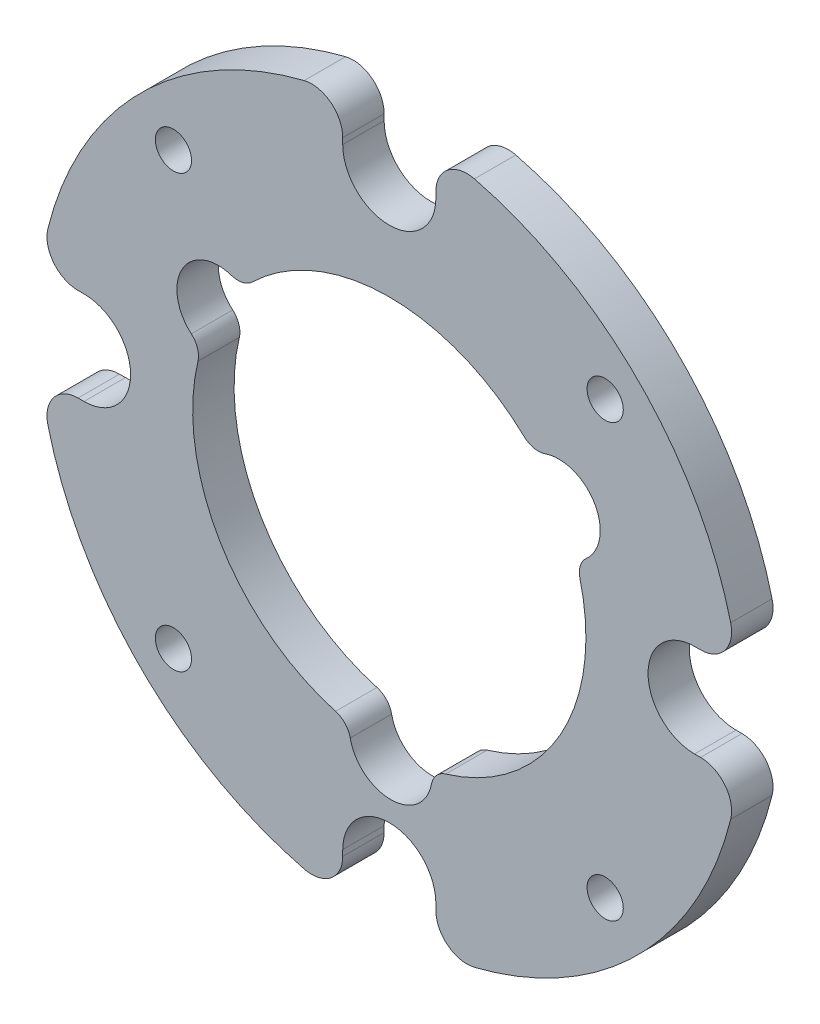
SolidWorks part; units mm, degrees
ref_plane "Спереди" through (0, 0, 0) normal (0, 0, 1) x (1, 0, 0)
ref_plane "Сверху" through (0, 0, 0) normal (0, 1, 0) x (1, 0, 0)
ref_plane "Справа" through (0, 0, 0) normal (1, 0, 0) x (0, 0, -1)
sketch "Sketch1" plane through (0, 0, 0) normal (0, 0, 1) x (1, 0, 0)
  line L0 (3.9, 6.755) -> (7.8, 0) construction
  line L2 (5.85, 10.1325) -> (11.7, 0) construction
  line L4 (7.8, 13.51) -> (15.6, 0) construction
  circle A61 centre (0, 0) radius 20
  circle A131 centre (0, 0) radius 1.25
  circle A484 centre (3.9, 0) radius 1.25
  circle A485 centre (7.8, 0) radius 1.25
  circle A486 centre (11.7, 0) radius 1.25
  circle A487 centre (15.6, 0) radius 1.25
  circle A488 centre (1.95, -3.3775) radius 1.25
  circle A489 centre (3.9, -6.755) radius 1.25
  circle A490 centre (5.85, -10.1325) radius 1.25
  circle A491 centre (7.8, -13.51) radius 1.25
  circle A492 centre (-1.95, -3.3775) radius 1.25
  circle A493 centre (-3.9, -6.755) radius 1.25
  circle A494 centre (-5.85, -10.1325) radius 1.25
  circle A495 centre (-7.8, -13.51) radius 1.25
  circle A496 centre (-3.9, 0) radius 1.25
  circle A497 centre (-7.8, 0) radius 1.25
  circle A498 centre (-11.7, 0) radius 1.25
  circle A499 centre (-15.6, 0) radius 1.25
  circle A500 centre (-1.95, 3.3775) radius 1.25
  circle A501 centre (-3.9, 6.755) radius 1.25
  circle A502 centre (-5.85, 10.1325) radius 1.25
  circle A503 centre (-7.8, 13.51) radius 1.25
  circle A504 centre (1.95, 3.3775) radius 1.25
  circle A505 centre (3.9, 6.755) radius 1.25
  circle A506 centre (5.85, 10.1325) radius 1.25
  circle A507 centre (7.8, 13.51) radius 1.25
  circle A508 centre (5.85, 3.3775) radius 1.25
  circle A509 centre (7.8, 6.755) radius 1.25
  circle A510 centre (9.75, 3.3775) radius 1.25
  circle A511 centre (11.7, 6.755) radius 1.25
  circle A512 centre (9.7491, 10.1341) radius 1.25
  circle A513 centre (13.6509, 3.3759) radius 1.25
  circle A514 centre (5.85, -3.3791) radius 1.25
  circle A515 centre (9.75, -3.3791) radius 1.25
  circle A516 centre (7.8, -6.7566) radius 1.25
  circle A517 centre (11.7, -6.7566) radius 1.25
  circle A518 centre (9.7491, -10.1356) radius 1.25
  circle A519 centre (13.6509, -3.3775) radius 1.25
  circle A520 centre (-0.0013, -6.7573) radius 1.25
  circle A521 centre (1.9487, -10.1348) radius 1.25
  circle A522 centre (-1.9513, -10.1348) radius 1.25
  circle A523 centre (-0.0013, -13.5123) radius 1.25
  circle A524 centre (-3.9032, -13.5123) radius 1.25
  circle A525 centre (3.9005, -13.5123) radius 1.25
  circle A526 centre (-5.8527, -3.3791) radius 1.25
  circle A527 centre (-7.8027, -6.7566) radius 1.25
  circle A528 centre (-9.7527, -3.3791) radius 1.25
  circle A529 centre (-11.7027, -6.7566) radius 1.25
  circle A530 centre (-13.6536, -3.3775) radius 1.25
  circle A531 centre (-9.7518, -10.1356) radius 1.25
  circle A532 centre (-5.8527, 3.3775) radius 1.25
  circle A533 centre (-9.7527, 3.3775) radius 1.25
  circle A534 centre (-7.8027, 6.755) radius 1.25
  circle A535 centre (-11.7027, 6.755) radius 1.25
  circle A536 centre (-9.7518, 10.1341) radius 1.25
  circle A537 centre (-13.6536, 3.3759) radius 1.25
  circle A538 centre (-0.0014, 6.7558) radius 1.25
  circle A539 centre (-1.9514, 10.1333) radius 1.25
  circle A540 centre (1.9486, 10.1333) radius 1.25
  circle A541 centre (-0.0014, 13.5108) radius 1.25
  circle A542 centre (3.9005, 13.5108) radius 1.25
  circle A543 centre (-3.9032, 13.5108) radius 1.25
  circle A544 centre (13.65, -1.1258) radius 2.2517 construction
  circle A545 centre (11.7009, -4.5044) radius 2.2522 construction
  circle A546 centre (9.75, -7.8834) radius 2.2522 construction
  circle A547 centre (7.7987, -11.2591) radius 2.2509 construction
  circle A548 centre (13.65, -1.1258) radius 0.65
  circle A549 centre (11.7009, -4.5044) radius 0.65
  circle A550 centre (9.75, -7.8834) radius 0.65
  circle A551 centre (7.7987, -11.2591) radius 0.65
  circle A552 centre (9.75, -1.1258) radius 0.65
  circle A553 centre (7.8009, -4.5044) radius 0.65
  circle A554 centre (5.85, -7.8834) radius 0.65
  circle A555 centre (3.8987, -11.2591) radius 0.65
  circle A556 centre (5.85, -1.1258) radius 0.65
  circle A557 centre (3.9009, -4.5044) radius 0.65
  circle A558 centre (1.95, -7.8834) radius 0.65
  circle A559 centre (-0.0013, -11.2591) radius 0.65
  circle A560 centre (1.95, -1.1258) radius 0.65
  circle A561 centre (0.0009, -4.5044) radius 0.65
  circle A562 centre (-1.95, -7.8834) radius 0.65
  circle A563 centre (-3.9013, -11.2591) radius 0.65
  circle A564 centre (-1.95, -1.1258) radius 0.65
  circle A565 centre (-3.8991, -4.5044) radius 0.65
  circle A566 centre (-5.85, -7.8834) radius 0.65
  circle A567 centre (-7.8013, -11.2591) radius 0.65
  circle A568 centre (-5.85, -1.1258) radius 0.65
  circle A569 centre (-7.7991, -4.5044) radius 0.65
  circle A570 centre (-9.75, -7.8834) radius 0.65
  circle A572 centre (-9.75, -1.1258) radius 0.65
  circle A573 centre (-11.6991, -4.5044) radius 0.65
  circle A576 centre (-13.65, -1.1258) radius 0.65
  circle A580 centre (-15.5991, -4.5044) radius 0.65 [skipped]
  circle A581 centre (-13.65, -7.8834) radius 0.65 [skipped]
  circle A582 centre (-17.55, -7.8834) radius 0.65 [skipped]
  circle A583 centre (-19.5013, -11.2591) radius 0.65 [skipped]
  circle A584 centre (-15.6013, -11.2591) radius 0.65 [skipped]
  circle A585 centre (-11.7013, -11.2591) radius 0.65 [skipped]
  circle A587 centre (0, 2.2517) radius 2.2517 construction
  circle A588 centre (0, 2.2517) radius 0.65
  circle A589 centre (3.9, 2.2517) radius 0.65
  circle A590 centre (7.8, 2.2517) radius 0.65
  circle A591 centre (11.7, 2.2517) radius 0.65
  circle A592 centre (15.6, 2.2517) radius 0.65
  circle A593 centre (1.9491, 5.6297) radius 2.2522 construction
  circle A594 centre (1.9491, 5.6297) radius 0.65
  circle A595 centre (5.8491, 5.6297) radius 0.65
  circle A596 centre (9.7491, 5.6297) radius 0.65
  circle A597 centre (13.6491, 5.6297) radius 0.65
  circle A598 centre (3.8991, 9.0072) radius 2.2522 construction
  circle A599 centre (3.8991, 9.0072) radius 0.65
  circle A600 centre (7.7991, 9.0072) radius 0.65
  circle A601 centre (11.6991, 9.0072) radius 0.65
  circle A602 centre (5.85, 12.3842) radius 2.2517 construction
  circle A603 centre (5.85, 12.3842) radius 0.65
  circle A604 centre (9.75, 12.3842) radius 0.65
  circle A605 centre (5.85, -14.6358) radius 0.65
  circle A606 centre (1.9509, -14.6353) radius 0.65
  circle A607 centre (-1.9491, -14.6353) radius 0.65
  circle A608 centre (-5.85, -14.6358) radius 0.65
  circle A609 centre (-15.6, 2.2517) radius 0.65
  circle A610 centre (-13.65, 5.6281) radius 0.65
  circle A611 centre (-11.7, 9.0056) radius 0.65
  circle A612 centre (-9.75, 12.3842) radius 0.65
  circle A613 centre (-5.85, 12.3842) radius 0.65
  circle A614 centre (-1.95, 12.3842) radius 0.65
  circle A615 centre (1.95, 12.3842) radius 0.65
  circle A616 centre (-7.8, 9.0056) radius 0.65
  circle A617 centre (-9.75, 5.6281) radius 0.65
  circle A618 centre (-11.7, 2.2517) radius 0.65
  circle A619 centre (-3.9, 9.0056) radius 0.65
  circle A620 centre (-5.85, 5.6281) radius 0.65
  circle A621 centre (-7.8, 2.2517) radius 0.65
  circle A622 centre (0, 9.0056) radius 0.65
  circle A623 centre (-1.95, 5.6281) radius 0.65
  circle A624 centre (-3.9, 2.2517) radius 0.65
  point P51 (0, 0)
  point P125 (-0.0013, -0.0008)
  point P231 (0, 0)
  dimension "D1" = 5
  dimension "D3" = 6
  dimension "D5" = 8
  dimension "D7" = 4
  dimension "D2" = 6
  dimension "D6" = 5
  dimension "D8" = 3
  dimension "D9" = 2
  dimension "D4" = 1.3
  dimension "D10" = 3
sketch "Sketch5" plane through (0, 0, 0) normal (0, 0, 1) x (1, 0, 0)
  circle A0 centre (0, 0) radius 23.5 construction
  circle A1 centre (0, 0) radius 34
  circle A2 centre (0, 0) radius 19
extrude "Boss-Extrude1" add sketch "Sketch5" against normal blind 4
sketch "Sketch8" plane through (0, 0, 0) normal (0, 0, 1) x (1, 0, 0)
  line L0 (0, 0) -> (-19.915, 0)
  line L1 (0, 0) -> (-20.8597, 20.8597) construction
  circle A0 centre (0, 0) radius 29.5 construction
  circle A1 centre (-20.8597, 20.8597) radius 1.75
  circle A2 centre (20.8597, 20.8597) radius 1.75
  circle A3 centre (20.8597, -20.8597) radius 1.75
  circle A4 centre (-20.8597, -20.8597) radius 1.75
  point P15 (0, 0)
  dimension "D1" = 4
extrude "Cut-Extrude3" cut sketch "Sketch8" against normal blind 5 contours A2 | A1 | A4 | A3
sketch "Sketch27" plane through (0, 0, 0) normal (0, 0, 1) x (1, 0, 0)
  circle A0 centre (0, 0) radius 29.5 construction
  circle A1 centre (0, 29.5) radius 1.75
  circle A2 centre (29.5, 0) radius 1.75
  circle A3 centre (0, -29.5) radius 1.75
  circle A4 centre (-29.5, 0) radius 1.75
  point P15 (0, 0)
extrude "Cut-Extrude9" cut sketch "Sketch27" against normal blind 5
sketch "Sketch28" plane through (0, 0, 0) normal (0, 0, 1) x (1, 0, 0)
  line L0 (-4.5, 29.5) -> (-4.5, 40.0499)
  line L1 (-4.5, 40.0499) -> (4.5, 40.0499)
  line L2 (4.5, 40.0499) -> (4.5, 29.5)
  circle A0 centre (0, 29.5) radius 4.5
  circle M2 centre (0, 29.5) radius 1.75
  circle M11 centre (0, 0) radius 34
extrude "Cut-Extrude10" cut sketch "Sketch28" against normal blind 10 contours L2 L1 L0 M11 | A0 L0 M11 | A0 L2 M11 | A0 M2
fillet "Fillet1" radius 3 2 edges at (-4.5, 33.7009, -2) (4.5, 33.7009, -2)
pattern_circular "CirPattern1" count 4 over 360 about axis through (0, 0, 0) along (0, 0, 1) of "Cut-Extrude10", "Fillet1"
sketch "Sketch29" plane through (0, 0, 0) normal (0, 0, 1) x (1, 0, 0)
  circle A0 centre (0, 0) radius 19
  circle A1 centre (0, 0) radius 21.2
  dimension "D1" = 2.2
sketch "Sketch32" plane through (0, 0, 0) normal (0, 0, 1) x (1, 0, 0)
  circle A0 centre (-16.5249, 9.377) radius 4
  arc A1 (-13.6652, 13.2009) -> (-18.3409, 4.9609) centre (0, 0) ccw construction
  circle A4 centre (16.3832, 9.6225) radius 4
  circle A5 centre (0.1417, -18.9995) radius 4
  point P11 (0, 0)
  dimension "D1" = 3
extrude "Cut-Extrude11" cut sketch "Sketch32" against normal blind 10
fillet "Fillet2" radius 2 6 edges at (18.0346, 5.9793, -2) (14.0056, 12.8392, -2) (-3.8391, -18.6081, -2) (4.1163, -18.5488, -2) (-14.1956, 12.6288, -2) (-18.1218, 5.7096, -2)
